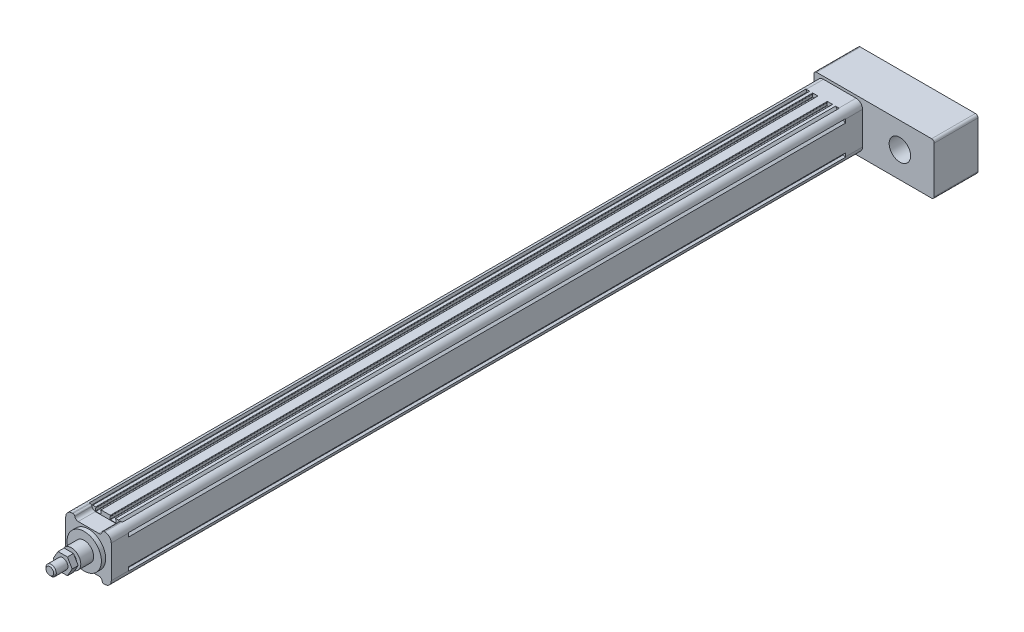
SolidWorks part; units mm, degrees
ref_plane "Front" through (0, 0, 0) normal (0, 0, 1) x (1, 0, 0)
ref_plane "Top" through (0, 0, 0) normal (0, 1, 0) x (1, 0, 0)
ref_plane "Right" through (0, 0, 0) normal (1, 0, 0) x (0, 0, -1)
sketch "草图1" plane through (0, 0, 0) normal (0, 0, 1) x (1, 0, 0)
  line L0 (19.7737, 3) -> (23.3, 3)
  line L1 (23.3, 3) -> (23.3, -3)
  line L2 (23.3, -3) -> (19.7737, -3)
  line L3 (-19.7737, -3) -> (-23.3, -3)
  line L4 (-23.3, -3) -> (-23.3, 3)
  line L5 (-23.3, 3) -> (-19.7737, 3)
  line L6 (-18.2, 24) -> (-19.4434, 26.4869)
  line L7 (-26.4869, 19.4434) -> (-24, 18.2)
  line L8 (-24, 18.2) -> (-24, 17.1)
  line L9 (-24, 17.1) -> (-26.5, 15)
  line L10 (-26.5, 15) -> (-26.5, -15)
  line L11 (-26.5, -15) -> (-24, -17.1)
  line L12 (-24, -17.1) -> (-24, -18.2)
  line L13 (-24, -18.2) -> (-26.4869, -19.4434)
  line L14 (-19.4434, -26.4869) -> (-18.2, -24)
  line L15 (-18.2, -24) -> (-17.1, -24)
  line L16 (-17.1, -24) -> (-15, -26.5)
  line L17 (-15, -26.5) -> (-11.65, -26.5)
  line L18 (-11.25, -26.1) -> (-11.25, -25.6)
  line L19 (-11.65, -25.2) -> (-11.75, -25.2)
  line L20 (-11.75, -25.2) -> (-11.75, -22.4)
  line L21 (-11.35, -22) -> (-5.65, -22)
  line L22 (-5.25, -22.4) -> (-5.25, -25.2)
  line L23 (-5.25, -25.2) -> (-5.35, -25.2)
  line L24 (-5.75, -25.6) -> (-5.75, -26.1)
  line L25 (-5.35, -26.5) -> (5.35, -26.5)
  line L26 (5.75, -26.1) -> (5.75, -25.6)
  line L27 (5.35, -25.2) -> (5.25, -25.2)
  line L28 (5.25, -25.2) -> (5.25, -22.4)
  line L29 (5.65, -22) -> (11.35, -22)
  line L30 (11.75, -22.4) -> (11.75, -25.2)
  line L31 (11.75, -25.2) -> (11.65, -25.2)
  line L32 (11.25, -25.6) -> (11.25, -26.1)
  line L33 (11.65, -26.5) -> (15, -26.5)
  line L34 (15, -26.5) -> (17.1, -24)
  line L35 (17.1, -24) -> (18.2, -24)
  line L36 (18.2, -24) -> (19.4434, -26.4869)
  line L37 (26.4869, -19.4434) -> (24, -18.2)
  line L38 (24, -18.2) -> (24, -17.1)
  line L39 (24, -17.1) -> (26.5, -15)
  line L40 (26.5, -15) -> (26.5, 15)
  line L41 (26.5, 15) -> (24, 17.1)
  line L42 (24, 17.1) -> (24, 18.2)
  line L43 (24, 18.2) -> (26.4869, 19.4434)
  line L44 (19.4434, 26.4869) -> (18.2, 24)
  line L45 (18.2, 24) -> (17.1, 24)
  line L46 (17.1, 24) -> (15, 26.5)
  line L47 (15, 26.5) -> (11.65, 26.5)
  line L48 (11.25, 26.1) -> (11.25, 25.6)
  line L49 (11.65, 25.2) -> (11.75, 25.2)
  line L50 (11.75, 25.2) -> (11.75, 22.4)
  line L51 (11.35, 22) -> (5.65, 22)
  line L52 (5.25, 22.4) -> (5.25, 25.2)
  line L53 (5.25, 25.2) -> (5.35, 25.2)
  line L54 (5.75, 25.6) -> (5.75, 26.1)
  line L55 (5.35, 26.5) -> (-5.35, 26.5)
  line L56 (-5.75, 26.1) -> (-5.75, 25.6)
  line L57 (-5.35, 25.2) -> (-5.25, 25.2)
  line L58 (-5.25, 25.2) -> (-5.25, 22.4)
  line L59 (-5.65, 22) -> (-11.35, 22)
  line L60 (-11.75, 22.4) -> (-11.75, 25.2)
  line L61 (-11.75, 25.2) -> (-11.65, 25.2)
  line L62 (-11.25, 25.6) -> (-11.25, 26.1)
  line L63 (-11.65, 26.5) -> (-15, 26.5)
  line L64 (-15, 26.5) -> (-17.1, 24)
  line L65 (-17.1, 24) -> (-18.2, 24)
  arc A0 (19.7737, 3) -> (-19.7737, 3) centre (0, 0) ccw
  arc A1 (-19.7737, -3) -> (19.7737, -3) centre (0, 0) ccw
  circle A2 centre (19, 19) radius 2.1
  circle A3 centre (19, -19) radius 2.1
  circle A4 centre (-19, -19) radius 2.1
  circle A5 centre (-19, 19) radius 2.1
  arc A6 (-19.4434, 26.4869) -> (-26.4869, 19.4434) centre (-19, 19) ccw
  arc A7 (-26.4869, -19.4434) -> (-19.4434, -26.4869) centre (-19, -19) ccw
  arc A8 (-11.65, -26.5) -> (-11.25, -26.1) centre (-11.65, -26.1) ccw
  arc A9 (-11.25, -25.6) -> (-11.65, -25.2) centre (-11.65, -25.6) ccw
  arc A10 (-11.35, -22) -> (-11.75, -22.4) centre (-11.35, -22.4) ccw
  arc A11 (-5.25, -22.4) -> (-5.65, -22) centre (-5.65, -22.4) ccw
  arc A12 (-5.35, -25.2) -> (-5.75, -25.6) centre (-5.35, -25.6) ccw
  arc A13 (-5.75, -26.1) -> (-5.35, -26.5) centre (-5.35, -26.1) ccw
  arc A14 (5.35, -26.5) -> (5.75, -26.1) centre (5.35, -26.1) ccw
  arc A15 (5.75, -25.6) -> (5.35, -25.2) centre (5.35, -25.6) ccw
  arc A16 (5.65, -22) -> (5.25, -22.4) centre (5.65, -22.4) ccw
  arc A17 (11.75, -22.4) -> (11.35, -22) centre (11.35, -22.4) ccw
  arc A18 (11.65, -25.2) -> (11.25, -25.6) centre (11.65, -25.6) ccw
  arc A19 (11.25, -26.1) -> (11.65, -26.5) centre (11.65, -26.1) ccw
  arc A20 (19.4434, -26.4869) -> (26.4869, -19.4434) centre (19, -19) ccw
  arc A21 (26.4869, 19.4434) -> (19.4434, 26.4869) centre (19, 19) ccw
  arc A22 (11.65, 26.5) -> (11.25, 26.1) centre (11.65, 26.1) ccw
  arc A23 (11.25, 25.6) -> (11.65, 25.2) centre (11.65, 25.6) ccw
  arc A24 (11.35, 22) -> (11.75, 22.4) centre (11.35, 22.4) ccw
  arc A25 (5.25, 22.4) -> (5.65, 22) centre (5.65, 22.4) ccw
  arc A26 (5.35, 25.2) -> (5.75, 25.6) centre (5.35, 25.6) ccw
  arc A27 (5.75, 26.1) -> (5.35, 26.5) centre (5.35, 26.1) ccw
  arc A28 (-5.35, 26.5) -> (-5.75, 26.1) centre (-5.35, 26.1) ccw
  arc A29 (-5.75, 25.6) -> (-5.35, 25.2) centre (-5.35, 25.6) ccw
  arc A30 (-5.65, 22) -> (-5.25, 22.4) centre (-5.65, 22.4) ccw
  arc A31 (-11.75, 22.4) -> (-11.35, 22) centre (-11.35, 22.4) ccw
  arc A32 (-11.65, 25.2) -> (-11.25, 25.6) centre (-11.65, 25.6) ccw
  arc A33 (-11.25, 26.1) -> (-11.65, 26.5) centre (-11.65, 26.1) ccw
extrude "凸台-拉伸1" add sketch "草图1" along normal blind 835
sketch "草图6" plane through (0, 0, 835) normal (0, 0, 1) x (1, 0, 0)
  line L0 (0, 0) -> (19, 0) construction
  line L2 (-26.5, -19) -> (-26.5, 19)
  line L3 (-19, 26.5) -> (-17.9161, 26.5)
  line L4 (26.5, -19) -> (26.5, 19)
  line L5 (-26.5, -26.5) -> (26.5, 26.5) construction
  line L6 (-26.5, 26.5) -> (26.5, -26.5) construction
  line L7 (-12, 21.5) -> (12, 21.5)
  line L9 (19, 26.5) -> (17.9161, 26.5)
  line L10 (19, -26.5) -> (17.9161, -26.5)
  line L11 (-12, -21.5) -> (12, -21.5)
  line L12 (-19, -26.5) -> (-17.9161, -26.5)
  arc A0 (12, 21.5) -> (15.9441, 24.8333) centre (12, 25.5) ccw
  arc A1 (-15.9441, 24.8333) -> (-12, 21.5) centre (-12, 25.5) ccw
  arc A2 (-15.9441, 24.8333) -> (-17.9161, 26.5) centre (-17.9161, 24.5) ccw
  arc A3 (15.9441, 24.8333) -> (17.9161, 26.5) centre (17.9161, 24.5) cw
  arc A4 (-26.5, -19) -> (-19, -26.5) centre (-19, -19) ccw
  arc A5 (19, -26.5) -> (26.5, -19) centre (19, -19) ccw
  arc A6 (26.5, 19) -> (19, 26.5) centre (19, 19) ccw
  arc A7 (-26.5, 19) -> (-19, 26.5) centre (-19, 19) cw
  arc A8 (15.9441, -24.8333) -> (17.9161, -26.5) centre (17.9161, -24.5) ccw
  arc A9 (12, -21.5) -> (15.9441, -24.8333) centre (12, -25.5) cw
  arc A10 (-15.9441, -24.8333) -> (-12, -21.5) centre (-12, -25.5) cw
  arc A11 (-15.9441, -24.8333) -> (-17.9161, -26.5) centre (-17.9161, -24.5) cw
  point P0 (0, 0)
  point P9 (0, 21.5)
  point P13 (20, 20.8461)
  point P16 (-12, 20.8461)
  dimension "D5" = 4
  dimension "D6" = 2
  dimension "D7" = 2
  dimension "D9" = 7.5
  dimension "D1" = 53
  dimension "D2" = 53
  dimension "D3" = 26.5
  dimension "D4" = 24
  dimension "D8" = 5
extrude "凸台-拉伸2" add sketch "草图6" along normal blind 20
sketch "草图7" plane through (0, 0, 855) normal (0, 0, 1) x (1, 0, 0)
  circle A0 centre (0, 0) radius 20
  dimension "D1" = 40
extrude "凸台-拉伸3" add sketch "草图7" along normal blind 5
sketch "草图9" plane through (0, 0, 860) normal (0, 0, 1) x (1, 0, 0)
  circle A0 centre (0, 0) radius 11
  dimension "D1" = 22
extrude "凸台-拉伸4" add sketch "草图9" along normal blind 15
sketch "草图10" plane through (0, 0, 875) normal (0, 0, 1) x (1, 0, 0)
  circle A0 centre (0, 0) radius 6
  dimension "D1" = 12
extrude "凸台-拉伸5" add sketch "草图10" along normal blind 25
sketch "草图11" plane through (0, 0, 0) normal (0, 0, -1) x (-1, 0, 0)
  line L1 (-19, -26.5) -> (19, -26.5)
  line L2 (-26.5, -19) -> (-26.5, 19)
  line L3 (-19, 26.5) -> (19, 26.5)
  line L4 (26.5, -19) -> (26.5, 19)
  line L5 (-26.5, -26.5) -> (26.5, 26.5) construction
  line L6 (-26.5, 26.5) -> (26.5, -26.5) construction
  arc A0 (-26.5, -19) -> (-19, -26.5) centre (-19, -19) ccw
  arc A1 (19, -26.5) -> (26.5, -19) centre (19, -19) ccw
  arc A2 (26.5, 19) -> (19, 26.5) centre (19, 19) ccw
  arc A3 (-26.5, 19) -> (-19, 26.5) centre (-19, 19) cw
  point P0 (0, 0)
  dimension "D3" = 7.5
  dimension "D1" = 53
  dimension "D2" = 53
extrude "凸台-拉伸6" add sketch "草图11" along normal blind 20
sketch "草图12" plane through (0, 0, -20) normal (0, 0, -1) x (-1, 0, 0)
  line L1 (-107, -30.4042) -> (27, -30.4042)
  line L2 (-110, -27.4042) -> (-110, 26.5958)
  line L3 (-107, 29.5958) -> (27, 29.5958)
  line L4 (30, -27.4042) -> (30, 26.5958)
  line L5 (-110, -30.4042) -> (30, 29.5958) construction
  line L6 (-110, 29.5958) -> (30, -30.4042) construction
  arc A0 (27, 29.5958) -> (30, 26.5958) centre (27, 26.5958) cw
  arc A1 (30, -27.4042) -> (27, -30.4042) centre (27, -27.4042) cw
  arc A2 (-110, -27.4042) -> (-107, -30.4042) centre (-107, -27.4042) ccw
  arc A3 (-110, 26.5958) -> (-107, 29.5958) centre (-107, 26.5958) cw
  point P0 (-40, -0.4042)
  dimension "D4" = 3
  dimension "D1" = 60
  dimension "D2" = 140
  dimension "D3" = 30
extrude "凸台-拉伸7" add sketch "草图12" along normal blind 51
sketch "草图13" plane through (0, 0, -20) normal (0, 0, 1) x (1, 0, 0)
  circle A0 centre (70, 0) radius 12.5
  dimension "D2" = 25
  dimension "D1" = 70
extrude "切除-拉伸2" cut sketch "草图13" against normal blind 30
hole_wizard "M6 螺纹孔1" positions "草图14" profile "草图15" tap size "M6" standard "GB"
sketch "草图14" plane through (0, 0, -71) normal (0, 0, -1) x (-1, 0, 0)
  line L0 (30, -27.4042) -> (30, 26.5958) construction
  point P0 (19, -19)
  dimension "D1" = 11
  dimension "D2" = 19
sketch "草图15" plane through (-19, -19, -71) normal (1, 0, 0) x (0, 1, 0)
  line L0 (0, 0) -> (0, 16.5022)
  line L1 (0, 16.5022) -> (2.5, 15)
  line L2 (2.5, 15) -> (2.5, 0)
  line L5 (2.5, 0) -> (0, 0)
  line L10 (0, 16.5022) -> (-2.5, 15) construction
  line L11 (0, -6.35) -> (0, 107.95) construction
  dimension "螺纹孔钻头直径" = 5
  dimension "螺纹孔钻头深度" = 15
  dimension "导头角度" = 118
cosmetic thread "孔螺蚊线4" parameters "D1"=12, "D2"=6
pattern_linear "阵列(线性)1" count 2 spacing 38 along (0, 1, 0) count 2 spacing 38 along (1, 0, 0) of "M6 螺纹孔1"
hole_wizard "M6 螺纹孔2" positions "草图16" profile "草图17" tap size "M6" standard "GB"
sketch "草图16" plane through (0, 0, -71) normal (0, 0, -1) x (-1, 0, 0)
  circle A1 centre (-19, 19) radius 2.5 construction
  circle A2 centre (-19, -19) radius 2.5 construction
  point P0 (-84, -19)
  point P2 (-84, 19)
  dimension "D3" = 65
  dimension "D1" = 19
  dimension "D2" = 19
  dimension "D4" = 65
sketch "草图17" plane through (84, -19, -71) normal (1, 0, 0) x (0, 1, 0)
  line L0 (0, 0) -> (0, 16.5022)
  line L1 (0, 16.5022) -> (2.5, 15)
  line L2 (2.5, 15) -> (2.5, 0)
  line L5 (2.5, 0) -> (0, 0)
  line L10 (0, 16.5022) -> (-2.5, 15) construction
  line L11 (0, -6.35) -> (0, 107.95) construction
  dimension "螺纹孔钻头直径" = 5
  dimension "螺纹孔钻头深度" = 15
  dimension "导头角度" = 118
cosmetic thread "孔螺蚊线5" parameters "D1"=12, "D2"=6
cosmetic thread "孔螺蚊线6" parameters "D1"=12, "D2"=6
hole_wizard "M6 螺纹孔3" positions "草图19" profile "草图20" tap size "M6" standard "GB"
sketch "草图19" plane through (-26.5, 0, 0) normal (-1, 0, 0) x (0, 0, 1)
  line L0 (855, 19) -> (855, -19) construction
  point P0 (845, 11)
  point P2 (845, -11)
  dimension "D1" = 10
  dimension "D2" = 10
  dimension "D3" = 22
  dimension "D4" = 11
sketch "草图20" plane through (-26.5, 11, 845) normal (0, 1, 0) x (0, 0, 1)
  line L0 (0, 0) -> (0, 16.5022)
  line L1 (0, 16.5022) -> (2.5, 15)
  line L2 (2.5, 15) -> (2.5, 0)
  line L5 (2.5, 0) -> (0, 0)
  line L10 (0, 16.5022) -> (-2.5, 15) construction
  line L11 (0, -6.35) -> (0, 107.95) construction
  dimension "螺纹孔钻头直径" = 5
  dimension "螺纹孔钻头深度" = 15
  dimension "导头角度" = 118
cosmetic thread "孔螺蚊线7" parameters "D1"=12, "D2"=6
cosmetic thread "孔螺蚊线8" parameters "D1"=12, "D2"=6
hole_wizard "M6 螺纹孔4" positions "草图21" profile "草图22" tap size "M6" standard "GB"
sketch "草图21" plane through (-26.5, 0, 0) normal (-1, 0, 0) x (0, 0, 1)
  line L0 (-20, -27.4042) -> (-20, 26.5958) construction
  line L1 (-20, -19) -> (-20, 19) construction
  point P0 (-10, 11)
  point P2 (-10, -11)
  dimension "D1" = 10
  dimension "D2" = 10
  dimension "D3" = 11
  dimension "D4" = 11
sketch "草图22" plane through (-26.5, 11, -10) normal (0, 1, 0) x (0, 0, 1)
  line L0 (0, 0) -> (0, 16.5022)
  line L1 (0, 16.5022) -> (2.5, 15)
  line L2 (2.5, 15) -> (2.5, 0)
  line L5 (2.5, 0) -> (0, 0)
  line L10 (0, 16.5022) -> (-2.5, 15) construction
  line L11 (0, -6.35) -> (0, 107.95) construction
  dimension "螺纹孔钻头直径" = 5
  dimension "螺纹孔钻头深度" = 15
  dimension "导头角度" = 118
cosmetic thread "孔螺蚊线9" parameters "D1"=12, "D2"=6
cosmetic thread "孔螺蚊线10" parameters "D1"=12, "D2"=6
chamfer "倒角1" distance 1.5 angle 45 1 edges at (6, 0, 900)
sketch "草图23" plane through (0, 0, 875) normal (0, 0, 1) x (1, 0, 0)
  line L1 (10.9697, 0) -> (5.4848, 9.5)
  line L2 (5.4848, 9.5) -> (-5.4848, 9.5)
  line L3 (-5.4848, 9.5) -> (-10.9697, 0)
  line L4 (-10.9697, 0) -> (-5.4848, -9.5)
  line L5 (-5.4848, -9.5) -> (5.4848, -9.5)
  line L6 (5.4848, -9.5) -> (10.9697, 0)
  circle A0 centre (0, 0) radius 9.5 construction
  dimension "D1" = 19
extrude "凸台-拉伸8" add sketch "草图23" along normal blind 7 from offset 3
